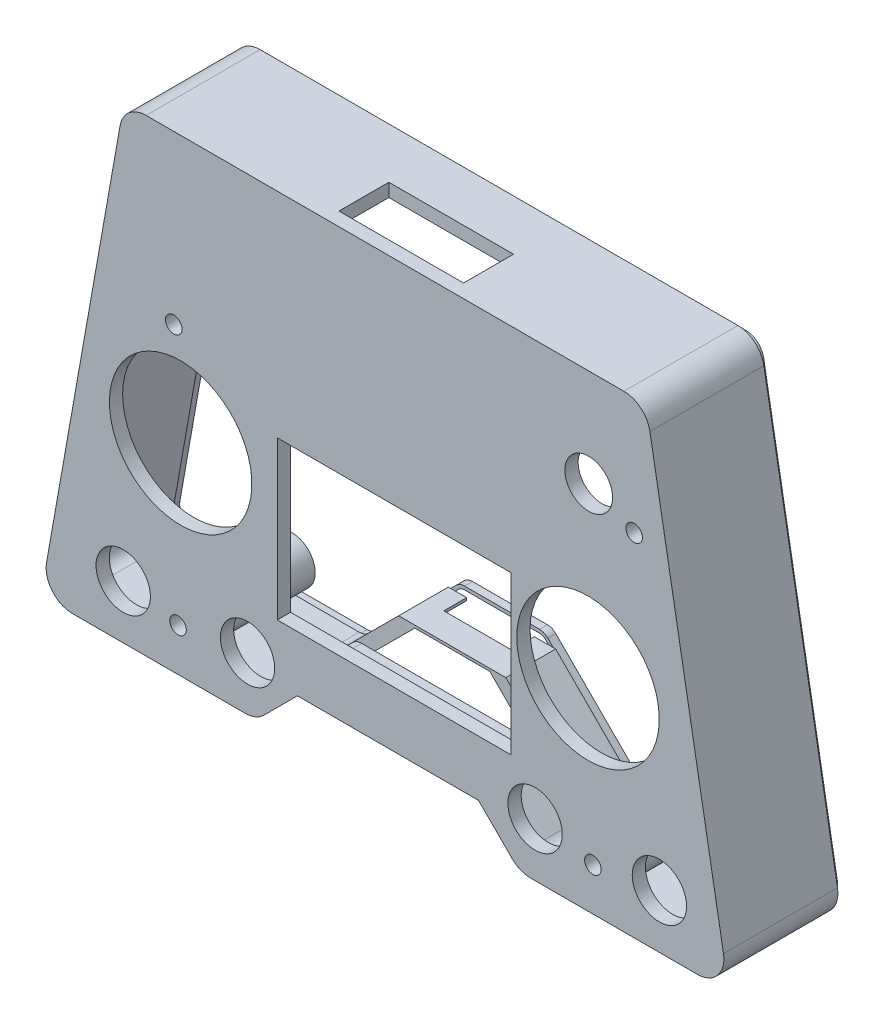
SolidWorks part; units mm, degrees
ref_plane "前视基准面" through (0, 0, 0) normal (0, 0, 1) x (1, 0, 0)
ref_plane "上视基准面" through (0, 0, 0) normal (0, 1, 0) x (1, 0, 0)
ref_plane "右视基准面" through (0, 0, 0) normal (1, 0, 0) x (0, 0, -1)
other "Configuration Table"
sketch "草图1" plane through (0, 0, 0) normal (0, 0, 1) x (1, 0, 0)
  line L0 (-11.561, 23.55) -> (-22.663, -39.125)
  line L1 (-18.737, -43.807) -> (7.32, -43.807)
  line L2 (10.139, -42.64) -> (23.192, -29.587)
  line L3 (23.201, -29.583) -> (34.512, -29.583)
  line L4 (34.521, -29.587) -> (47.574, -42.64)
  line L5 (50.393, -43.807) -> (75.552, -43.807)
  line L6 (79.479, -39.125) -> (68.376, 23.55)
  line L7 (64.45, 26.842) -> (-7.635, 26.842)
  arc A0 (-7.635, 26.842) -> (-11.561, 23.55) centre (-7.635, 22.855) ccw
  arc A1 (-22.663, -39.125) -> (-18.737, -43.807) centre (-18.737, -39.82) ccw
  arc A2 (7.32, -43.807) -> (10.139, -42.64) centre (7.3205, -39.8198) ccw
  arc A3 (23.192, -29.587) -> (23.201, -29.583) centre (23.2013, -29.5959) cw
  arc A4 (34.512, -29.583) -> (34.521, -29.587) centre (34.5117, -29.5959) cw
  arc A5 (47.574, -42.64) -> (50.393, -43.807) centre (50.3925, -39.8198) ccw
  arc A6 (75.552, -43.807) -> (79.479, -39.125) centre (75.5524, -39.8195) ccw
  arc A7 (68.376, 23.55) -> (64.45, 26.842) centre (64.45, 22.855) ccw
extrude "上壳外形_高17.2" add sketch "草图1" along normal blind 17.2
sketch "草图2" plane through (0, 0, 0) normal (0, 0, 1) x (1, 0, 0)
  line L0 (-11.561, 23.55) -> (-22.663, -39.125)
  line L1 (-18.737, -43.807) -> (7.32, -43.807)
  line L2 (10.139, -42.64) -> (15.192, -37.587)
  line L3 (15.201, -37.583) -> (42.512, -37.583)
  line L4 (42.521, -37.587) -> (47.574, -42.64)
  line L5 (50.393, -43.807) -> (75.552, -43.807)
  line L6 (79.479, -39.125) -> (68.376, 23.55)
  line L7 (64.45, 26.842) -> (-7.635, 26.842)
  arc A0 (-7.635, 26.842) -> (-11.561, 23.55) centre (-7.635, 22.855) ccw
  arc A1 (-22.663, -39.125) -> (-18.737, -43.807) centre (-18.737, -39.82) ccw
  arc A2 (7.32, -43.807) -> (10.139, -42.64) centre (7.3205, -39.8198) ccw
  arc A3 (15.192, -37.587) -> (15.201, -37.583) centre (15.2013, -37.5959) cw
  arc A4 (42.512, -37.583) -> (42.521, -37.587) centre (42.5117, -37.5959) cw
  arc A5 (47.574, -42.64) -> (50.393, -43.807) centre (50.3925, -39.8198) ccw
  arc A6 (75.552, -43.807) -> (79.479, -39.125) centre (75.5524, -39.8195) ccw
  arc A7 (68.376, 23.55) -> (64.45, 26.842) centre (64.45, 22.855) ccw
extrude "OLED前伸罩_下部避让USB" add sketch "草图2" along normal blind 9.7 from offset 7.5
sketch "草图3" plane through (0, 0, 0) normal (0, 0, 1) x (1, 0, 0)
  line L0 (-9.591, 23.202) -> (-20.693, -39.473)
  line L1 (-18.737, -41.807) -> (7.32, -41.807)
  line L2 (8.725, -41.226) -> (21.778, -28.173)
  line L3 (23.201, -27.583) -> (34.512, -27.583)
  line L4 (35.935, -28.173) -> (48.988, -41.226)
  line L5 (50.393, -41.807) -> (75.552, -41.807)
  line L6 (77.509, -39.473) -> (66.406, 23.202)
  line L7 (64.45, 24.842) -> (-7.635, 24.842)
  arc A0 (-7.635, 24.842) -> (-9.591, 23.202) centre (-7.6347, 22.8552) ccw
  arc A1 (-20.693, -39.473) -> (-18.737, -41.807) centre (-18.7368, -39.8202) ccw
  arc A2 (7.32, -41.807) -> (8.725, -41.226) centre (7.3208, -39.8197) ccw
  arc A3 (21.778, -28.173) -> (23.201, -27.583) centre (23.2017, -29.5957) cw
  arc A4 (34.512, -27.583) -> (35.935, -28.173) centre (34.5113, -29.5957) cw
  arc A5 (48.988, -41.226) -> (50.393, -41.807) centre (50.3922, -39.8197) ccw
  arc A6 (75.552, -41.807) -> (77.509, -39.473) centre (75.5522, -39.8197) ccw
  arc A7 (66.406, 23.202) -> (64.45, 24.842) centre (64.4497, 22.8552) ccw
extrude "内部腔体_壁厚2.0" cut sketch "草图3" along normal blind 15.2
sketch "草图4" plane through (0, 0, 0) normal (0, 0, 1) x (1, 0, 0)
  line L0 (-9.591, 23.202) -> (-20.693, -39.473)
  line L1 (-18.737, -41.807) -> (7.32, -41.807)
  line L2 (8.725, -41.226) -> (13.778, -36.173)
  line L3 (15.201, -35.583) -> (42.512, -35.583)
  line L4 (43.935, -36.173) -> (48.988, -41.226)
  line L5 (50.393, -41.807) -> (75.552, -41.807)
  line L6 (77.509, -39.473) -> (66.406, 23.202)
  line L7 (64.45, 24.842) -> (-7.635, 24.842)
  arc A0 (-7.635, 24.842) -> (-9.591, 23.202) centre (-7.6347, 22.8552) ccw
  arc A1 (-20.693, -39.473) -> (-18.737, -41.807) centre (-18.7368, -39.8202) ccw
  arc A2 (7.32, -41.807) -> (8.725, -41.226) centre (7.3208, -39.8197) ccw
  arc A3 (13.778, -36.173) -> (15.201, -35.583) centre (15.2017, -37.5957) cw
  arc A4 (42.512, -35.583) -> (43.935, -36.173) centre (42.5113, -37.5957) cw
  arc A5 (48.988, -41.226) -> (50.393, -41.807) centre (50.3922, -39.8197) ccw
  arc A6 (75.552, -41.807) -> (77.509, -39.473) centre (75.5522, -39.8197) ccw
  arc A7 (66.406, 23.202) -> (64.45, 24.842) centre (64.4497, 22.8552) ccw
extrude "OLED前伸内腔" cut sketch "草图4" along normal blind 7.7 from offset 7.5
sketch "草图5" plane through (0, 0, 0) normal (0, 0, 1) x (1, 0, 0)
  circle A0 centre (-3.469, 1.614) radius 2.5
  circle A1 centre (66, 9.107) radius 2.5
  circle A2 centre (-2.822, -37.375) radius 3.5
  circle A3 centre (59.778, -37.375) radius 3.5
extrude "螺钉柱_对齐底壳" add sketch "草图5" along normal blind 17.2
sketch "草图6" plane through (0, 0, 0) normal (0, 0, 1) x (1, 0, 0)
  circle A0 centre (-3.469, 1.614) radius 1.25
  circle A1 centre (66, 9.107) radius 1.25
  circle A2 centre (-2.822, -37.375) radius 1.25
  circle A3 centre (59.778, -37.375) radius 1.25
extrude "M3自攻底孔_直径2.5" cut sketch "草图6" along normal through all
sketch "草图7" plane through (0, 0, 0) normal (0, 0, 1) x (1, 0, 0)
  line L0 (79.479, -39.125) -> (68.376, 23.55) construction
  line L1 (66, 7.857) -> (70.7132, 7.857)
  line L2 (66, 7.857) -> (66, 10.357)
  line L3 (66, 10.357) -> (70.7132, 10.357)
  line L4 (70.7132, 7.857) -> (70.7132, 10.357)
  circle A0 centre (66, 9.107) radius 1.25 construction
extrude "右后螺钉柱侧向加强筋" add sketch "草图7" along normal blind 12.2 from offset 5
sketch "草图8" plane through (0, 0, 0) normal (0, 0, 1) x (1, 0, 0)
  circle A0 centre (59.353, 11.774) radius 6.2
extrude "拨杆开关螺母避让槽" cut sketch "草图8" along normal blind 5 from offset 9.9
sketch "草图9" plane through (0, 0, 0) normal (0, 0, 1) x (1, 0, 0)
  circle A0 centre (66, 9.107) radius 1.25
extrude "加强筋处螺钉底孔" cut sketch "草图9" along normal through all
sketch "草图10" plane through (0, 0, 0) normal (0, 0, 1) x (1, 0, 0)
  circle A0 centre (-2.427, -13.356) radius 10.75
  circle A1 centre (59.041, -13.356) radius 10.75
  circle A2 centre (-11.089, -35.723) radius 4.1
  circle A3 centre (7.669, -35.723) radius 4.1
  circle A4 centre (51.053, -35.723) radius 4.1
  circle A5 centre (69.81, -35.723) radius 4.1
  circle A6 centre (59.147, 12.097) radius 3.6
extrude "FrontPanel_Control_Openings" cut sketch "草图10" along normal through all
sketch "草图11" plane through (0, 0, 0) normal (0, 0, 1) x (1, 0, 0)
  line L1 (12.155, -29.185) -> (47.455, -29.185)
  line L2 (12.155, -29.185) -> (12.155, -5.385)
  line L3 (12.155, -5.385) -> (47.455, -5.385)
  line L4 (47.455, -29.185) -> (47.455, -5.385)
extrude "OLED_0p96_From_Header_Toward_TypeC" cut sketch "草图11" along normal through all
sketch "草图12" plane through (0, -29.583, 0) normal (0, -1, 0) x (1, 0, 0)
  line L0 (23.534, -1.55) -> (33.734, -1.55)
  line L1 (33.734, -1.55) -> (33.734, 3.45)
  line L2 (33.734, 3.45) -> (23.534, 3.45)
  line L3 (23.534, 3.45) -> (23.534, -1.55)
extrude "USB_TypeC_Side_Opening" cut sketch "草图12" against normal blind 4
sketch "草图13" plane through (-15.2539, 2.702, 0) normal (-0.9847, 0.1744, 0) x (0, 0, 1)
  line L0 (1, 14.6424) -> (1, 7.9925)
  line L1 (1, 7.9925) -> (5.6, 7.9925)
  line L2 (5.6, 7.9925) -> (5.6, 14.6424)
  line L3 (5.6, 14.6424) -> (1, 14.6424)
extrude "SW13_Toggle_Left_Side_Opening_2026-09-13_OBJ" cut sketch "草图13" against normal blind 4
sketch "草图14" plane through (0, 26.842, 0) normal (0, 1, 0) x (1, 0, 0)
  line L0 (19.41, -7.62) -> (38.21, -7.62)
  line L1 (38.21, -7.62) -> (38.21, -15.15)
  line L2 (38.21, -15.15) -> (19.41, -15.15)
  line L3 (19.41, -15.15) -> (19.41, -7.62)
extrude "NRF24_Corrected_2026-09-13_Rear_Opening" cut sketch "草图14" against normal blind 4
sketch "草图15" plane through (0, 0, 0) normal (0, 0, 1) x (1, 0, 0)
  line L0 (-10.3298, 23.3325) -> (-21.4318, -39.3425)
  line L1 (-18.737, -42.557) -> (7.32, -42.557)
  line L2 (9.2553, -41.7563) -> (22.3083, -28.7032)
  line L3 (23.201, -28.333) -> (34.512, -28.333)
  line L4 (35.4047, -28.7032) -> (48.4578, -41.7563)
  line L5 (50.393, -42.557) -> (75.552, -42.557)
  line L6 (78.2478, -39.3425) -> (67.1448, 23.3325)
  line L7 (64.45, 25.592) -> (-7.635, 25.592)
  line L8 (-9.8373, 23.2455) -> (-20.9393, -39.4295)
  line L9 (-18.737, -42.057) -> (7.32, -42.057)
  line L10 (8.9018, -41.4027) -> (21.9547, -28.3498)
  line L11 (23.201, -27.833) -> (34.512, -27.833)
  line L12 (35.7583, -28.3498) -> (48.8113, -41.4027)
  line L13 (50.393, -42.057) -> (75.552, -42.057)
  line L14 (77.7553, -39.4295) -> (66.6523, 23.2455)
  line L15 (64.45, 25.092) -> (-7.635, 25.092)
  arc A0 (-7.635, 25.592) -> (-10.3298, 23.3325) centre (-7.6348, 22.8551) ccw
  arc A1 (-21.4318, -39.3425) -> (-18.737, -42.557) centre (-18.7369, -39.8201) ccw
  arc A2 (7.32, -42.557) -> (9.2553, -41.7563) centre (7.3207, -39.8197) ccw
  arc A3 (22.3083, -28.7032) -> (23.201, -28.333) centre (23.2016, -29.5958) cw
  arc A4 (34.512, -28.333) -> (35.4047, -28.7032) centre (34.5114, -29.5958) cw
  arc A5 (48.4578, -41.7563) -> (50.393, -42.557) centre (50.3923, -39.8197) ccw
  arc A6 (75.552, -42.557) -> (78.2478, -39.3425) centre (75.5523, -39.8196) ccw
  arc A7 (67.1448, 23.3325) -> (64.45, 25.592) centre (64.4498, 22.8551) ccw
  arc A8 (-7.635, 25.092) -> (-9.8373, 23.2455) centre (-7.6348, 22.8552) ccw
  arc A9 (-20.9393, -39.4295) -> (-18.737, -42.057) centre (-18.7368, -39.8202) ccw
  arc A10 (7.32, -42.057) -> (8.9018, -41.4027) centre (7.3208, -39.8197) ccw
  arc A11 (21.9547, -28.3498) -> (23.201, -27.833) centre (23.2016, -29.5957) cw
  arc A12 (34.512, -27.833) -> (35.7583, -28.3498) centre (34.5114, -29.5957) cw
  arc A13 (48.8113, -41.4027) -> (50.393, -42.057) centre (50.3922, -39.8197) ccw
  arc A14 (75.552, -42.057) -> (77.7553, -39.4295) centre (75.5522, -39.8197) ccw
  arc A15 (66.6523, 23.2455) -> (64.45, 25.092) centre (64.4498, 22.8552) ccw
extrude "内定位舌_避让最新PCB_0.25" add sketch "草图15" against normal blind 1.2
